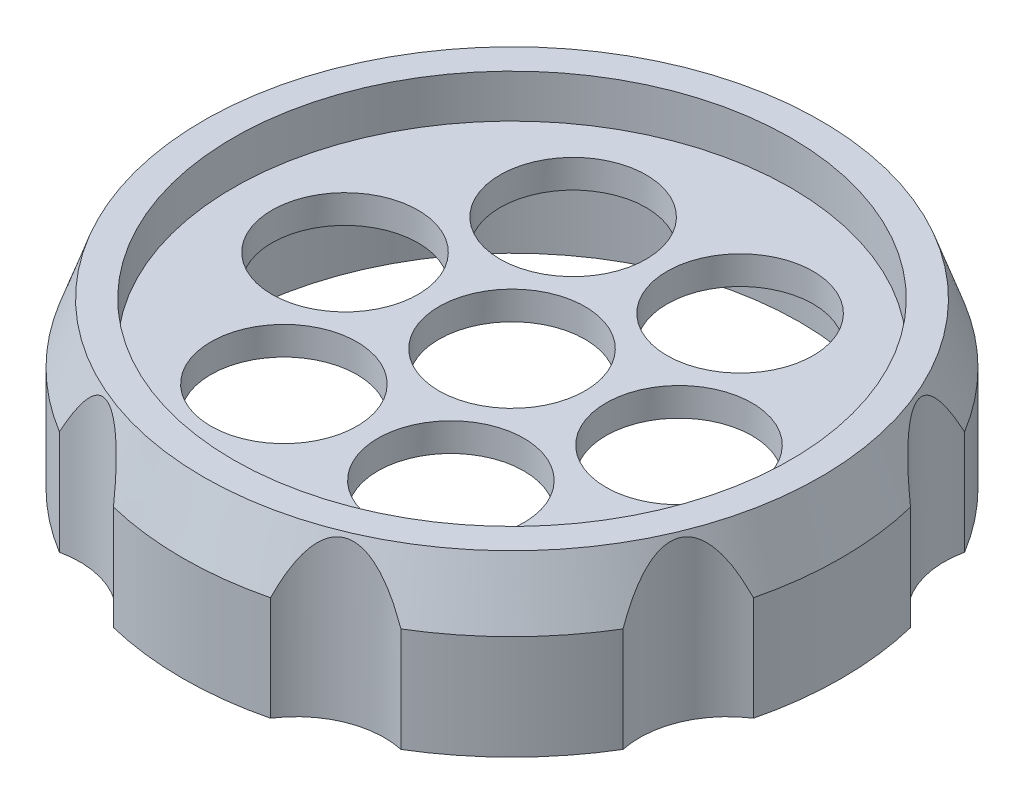
SolidWorks part; units mm, degrees
ref_plane "Front Plane" through (0, 0, 0) normal (0, 0, 1) x (1, 0, 0)
ref_plane "Top Plane" through (0, 0, 0) normal (0, 1, 0) x (1, 0, 0)
ref_plane "Right Plane" through (0, 0, 0) normal (1, 0, 0) x (0, 0, -1)
sketch "Croquis1" plane through (0, 0, 0) normal (0, 1, 0) x (1, 0, 0)
  circle A0 centre (0, 0) radius 11.05
  dimension "D1" = 22.1
extrude "Saliente-Extruir1" add sketch "Croquis1" along normal blind 5.5
chamfer "Chaflán1" distance 2 distance2 0.7 1 edges at (0, 5.5, 11.05)
sketch "Croquis2" plane through (0, 5.5, 0) normal (0, 1, 0) x (1, 0, 0)
  circle A0 centre (0, 0) radius 9.35
  dimension "D1" = 18.7
extrude "Cortar-Extruir1" cut sketch "Croquis2" against normal blind 1.45
sketch "Croquis3" plane through (0, 0, 0) normal (0, -1, 0) x (1, 0, 0)
  circle A0 centre (0, 0) radius 9.65
  dimension "D1" = 19.3
extrude "Cortar-Extruir2" cut sketch "Croquis3" against normal blind 3.1
sketch "Croquis4" plane through (0, 4.05, 0) normal (0, 1, 0) x (1, 0, 0)
  line L0 (0, 0) -> (11.05, 0) construction
  line L1 (5.6, 0) -> (2.8, 4.8497) construction
  line L2 (2.8, 4.8497) -> (-2.8, 4.8497) construction
  line L3 (-2.8, 4.8497) -> (-5.6, 0) construction
  line L4 (-5.6, 0) -> (-2.8, -4.8497) construction
  line L5 (-2.8, -4.8497) -> (2.8, -4.8497) construction
  line L6 (2.8, -4.8497) -> (5.6, 0) construction
  circle A0 centre (0, 0) radius 2.45
  circle A1 centre (0, 0) radius 4.8497 construction
  circle A2 centre (0, 0) radius 11.05 construction
  circle A3 centre (5.6, 0) radius 2.45
  circle A4 centre (2.8, 4.8497) radius 2.45
  circle A5 centre (-2.8, 4.8497) radius 2.45
  circle A6 centre (-5.6, 0) radius 2.45
  circle A7 centre (-2.8, -4.8497) radius 2.45
  circle A8 centre (2.8, -4.8497) radius 2.45
  point P14 (3.15, 0)
  point P15 (2.45, 0)
  dimension "D1" = 4.9
  dimension "D2" = 4.9
  dimension "D4" = 4.9
  dimension "D5" = 4.9
  dimension "D6" = 4.9
  dimension "D7" = 4.9
  dimension "D8" = 4.9
  dimension "D3" = 5.6
extrude "Cortar-Extruir3" cut sketch "Croquis4" against normal up to surface (0.95 mm away) up to face at (0, 3.1, -9.65)
sketch "Croquis5" plane through (0, 0, 0) normal (0, -1, 0) x (1, 0, 0)
  line L8 (0, 0) -> (0, -14.315) construction
  line L19 (5.1077, -12.331) -> (12.331, -5.1077) construction
  line L20 (12.331, -5.1077) -> (12.331, 5.1077) construction
  line L21 (12.331, 5.1077) -> (5.1077, 12.331) construction
  line L22 (5.1077, 12.331) -> (-5.1077, 12.331) construction
  line L23 (-5.1077, 12.331) -> (-12.331, 5.1077) construction
  line L24 (-12.331, 5.1077) -> (-12.331, -5.1077) construction
  line L25 (-12.331, -5.1077) -> (-5.1077, -12.331) construction
  line L26 (-5.1077, -12.331) -> (5.1077, -12.331) construction
  circle A8 centre (0, 0) radius 12.331 construction
  circle A9 centre (5.1077, 12.331) radius 2.9469
  circle A10 centre (12.331, 5.1077) radius 2.9469
  circle A11 centre (12.331, -5.1077) radius 2.9469
  circle A12 centre (5.1077, -12.331) radius 2.9469
  circle A13 centre (-5.1077, -12.331) radius 2.9469
  circle A14 centre (-12.331, -5.1077) radius 2.9469
  circle A15 centre (-12.331, 5.1077) radius 2.9469
  circle A16 centre (-5.1077, 12.331) radius 2.9469
  point P20 (0, -12.331)
  dimension "D2" = 5.8939
  dimension "D3" = 5.8939
  dimension "D4" = 5.8939
  dimension "D5" = 5.8939
  dimension "D6" = 5.8939
  dimension "D7" = 5.8939
  dimension "D8" = 5.8939
  dimension "D9" = 5.8939
  dimension "D17" = 13.3469
extrude "Cortar-Extruir4" cut sketch "Croquis5" against normal blind 7
